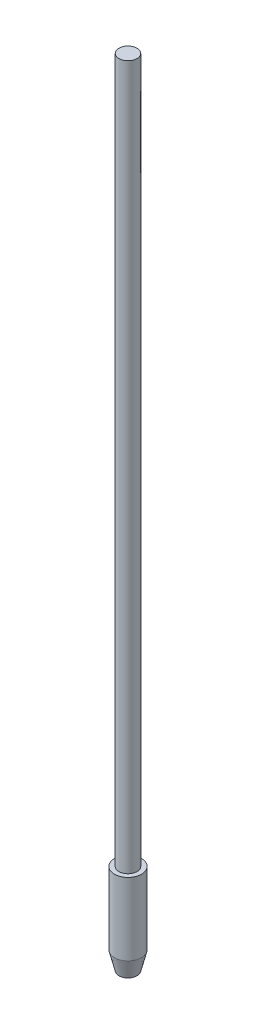
SolidWorks part; units mm, degrees
ref_plane "Front Plane" through (0, 0, 0) normal (0, 0, 1) x (1, 0, 0)
ref_plane "Top Plane" through (0, 0, 0) normal (0, 1, 0) x (1, 0, 0)
ref_plane "Right Plane" through (0, 0, 0) normal (1, 0, 0) x (0, 0, -1)
sketch "Sketch1" plane through (0, 0, 0) normal (0, 1, 0) x (1, 0, 0)
  line L0 (0, 0) -> (640, 0) construction
  line L1 (0, 0) -> (591.2829, 244.9174)
  line L2 (0, 0) -> (591.2829, -244.9174)
  line L3 (0, 0) -> (244.9174, -591.2829)
  line L4 (0, 0) -> (-244.9174, -591.2829)
  line L5 (0, 0) -> (-591.2829, -244.9174)
  line L6 (0, 0) -> (-591.2829, 244.9174)
  line L7 (0, 0) -> (-244.9174, 591.2829)
  line L8 (0, 0) -> (244.9174, 591.2829)
  line L9 (0, 145) -> (55, 145) construction
  line L10 (0, 0) -> (100, 0) construction
  line L11 (0, 0) -> (0, 145) construction
  line L14 (100, 0) -> (100, 145) construction
  circle A0 centre (0, 0) radius 640 construction
  point P15 (0, 0)
  dimension "D1" = 1280
  dimension "D2" = 22.5
  dimension "D4" = 145
  dimension "D5" = 100
  dimension "D6" = 55
  dimension "D3" = 8
sketch "Sketch2" plane through (0, 0, 0) normal (0, 1, 0) x (1, 0, 0)
  line L0 (-486.9956, 169.5033) -> (-66.9956, 169.5033) construction
  line L1 (-188.7141, -86.1278) -> (-188.7141, 241.8722) construction
  line L2 (525.6625, -1048.8053) -> (466.9027, -726.1115) construction
sketch "Sketch3" plane through (0, 0, 0) normal (0, 1, 0) x (1, 0, 0)
  line L0 (0, 0) -> (381.2468, 0) construction
  line L5 (0, 0) -> (0, 199.4415) construction
  line L6 (-10.2736, 158.9263) -> (10.2736, 158.9263)
  line L7 (10.2736, 158.9263) -> (13.1995, 163.9003)
  line L8 (13.1995, 163.9003) -> (45.5131, 148.2994)
  line L9 (45.5131, 148.2994) -> (66.2904, 80.9335)
  line L10 (66.2904, 80.9335) -> (73.8622, 80.9335)
  line L11 (73.8622, 80.9335) -> (86.8684, 42.4396)
  line L12 (86.8684, 42.4396) -> (86.8684, 30.0712)
  line L13 (86.8684, 30.0712) -> (81.3965, 24.5993)
  line L14 (81.3965, 24.5993) -> (81.3965, -24.5993)
  line L15 (-5.8349, 67.4929) -> (5.8349, 67.4929) construction
  line L16 (16.6008, 64.1674) -> (16.6008, 27.6557) construction
  line L17 (16.6008, 27.6557) -> (13.2646, 22.809) construction
  line L18 (13.2646, 22.809) -> (13.2646, -22.809) construction
  line L19 (5.8349, 128.0146) -> (5.8349, 107.4452)
  line L22 (5.8349, 107.4452) -> (9.2702, 107.4452)
  line L25 (9.2702, 107.4452) -> (10.663, 103.7163)
  line L26 (10.663, 103.7163) -> (20.7578, 101.0699)
  line L27 (20.7578, 101.0699) -> (32.199, 111.7601)
  line L28 (32.199, 111.7601) -> (32.199, 123.5038)
  line L29 (32.199, 123.5038) -> (24.9078, 123.5038)
  line L30 (24.9078, 123.5038) -> (13.8412, 132.5856)
  line L31 (13.8412, 132.5856) -> (9.2702, 132.5856)
  line L32 (9.2702, 132.5856) -> (5.8349, 128.0146)
  line L33 (41.9414, 39.7891) -> (51.4866, 54.1602)
  line L34 (51.4866, 54.1602) -> (55.4027, 54.1602)
  line L35 (55.4027, 54.1602) -> (58.1637, 51.3993)
  line L36 (58.1637, 51.3993) -> (58.1637, 43.1872)
  line L37 (58.1637, 43.1872) -> (66.3555, 28.462)
  line L38 (66.3555, 28.462) -> (66.3555, 24.0728)
  line L39 (66.3555, 24.0728) -> (62.2596, 17.9061)
  line L40 (62.2596, 17.9061) -> (47.8497, 18.1669)
  line L41 (47.8497, 18.1669) -> (41.9414, 27.1878)
  line L42 (41.9414, 27.1878) -> (41.9414, 39.7891)
  line L43 (-41.9414, 27.1878) -> (-41.9414, 39.7891)
  line L44 (-47.8497, 18.1669) -> (-41.9414, 27.1878)
  line L45 (-62.2596, 17.9061) -> (-47.8497, 18.1669)
  line L46 (-66.3555, 24.0728) -> (-62.2596, 17.9061)
  line L47 (-66.3555, 28.462) -> (-66.3555, 24.0728)
  line L48 (-58.1637, 43.1872) -> (-66.3555, 28.462)
  line L49 (-58.1637, 51.3993) -> (-58.1637, 43.1872)
  line L50 (-55.4027, 54.1602) -> (-58.1637, 51.3993)
  line L51 (-51.4866, 54.1602) -> (-55.4027, 54.1602)
  line L52 (-41.9414, 39.7891) -> (-51.4866, 54.1602)
  line L53 (-9.2702, 132.5856) -> (-5.8349, 128.0146)
  line L54 (-13.8412, 132.5856) -> (-9.2702, 132.5856)
  line L55 (-24.9078, 123.5038) -> (-13.8412, 132.5856)
  line L56 (-32.199, 123.5038) -> (-24.9078, 123.5038)
  line L57 (-32.199, 111.7601) -> (-32.199, 123.5038)
  line L58 (-20.7578, 101.0699) -> (-32.199, 111.7601)
  line L59 (-10.663, 103.7163) -> (-20.7578, 101.0699)
  line L60 (-9.2702, 107.4452) -> (-10.663, 103.7163)
  line L61 (-5.8349, 107.4452) -> (-9.2702, 107.4452)
  line L62 (-5.8349, 128.0146) -> (-5.8349, 107.4452)
  line L63 (-13.2646, 22.809) -> (-13.2646, -22.809) construction
  line L64 (-16.6008, 27.6557) -> (-13.2646, 22.809) construction
  line L65 (-16.6008, 64.1674) -> (-16.6008, 27.6557) construction
  line L66 (-81.3965, 24.5993) -> (-81.3965, -24.5993)
  line L67 (-86.8684, 30.0712) -> (-81.3965, 24.5993)
  line L68 (-86.8684, 42.4396) -> (-86.8684, 30.0712)
  line L69 (-73.8622, 80.9335) -> (-86.8684, 42.4396)
  line L70 (-66.2904, 80.9335) -> (-73.8622, 80.9335)
  line L71 (-45.5131, 148.2994) -> (-66.2904, 80.9335)
  line L72 (-13.1995, 163.9003) -> (-45.5131, 148.2994)
  line L73 (-10.2736, 158.9263) -> (-13.1995, 163.9003)
  line L74 (-10.2736, -158.9263) -> (-13.1995, -163.9003)
  line L75 (-13.1995, -163.9003) -> (-45.5131, -148.2994)
  line L76 (-45.5131, -148.2994) -> (-66.2904, -80.9335)
  line L77 (-66.2904, -80.9335) -> (-73.8622, -80.9335)
  line L78 (-73.8622, -80.9335) -> (-86.8684, -42.4396)
  line L79 (-86.8684, -42.4396) -> (-86.8684, -30.0712)
  line L80 (-86.8684, -30.0712) -> (-81.3965, -24.5993)
  line L81 (-16.6008, -64.1674) -> (-16.6008, -27.6557) construction
  line L82 (-16.6008, -27.6557) -> (-13.2646, -22.809) construction
  line L83 (-5.8349, -128.0146) -> (-5.8349, -107.4452)
  line L84 (-5.8349, -107.4452) -> (-9.2702, -107.4452)
  line L85 (-9.2702, -107.4452) -> (-10.663, -103.7163)
  line L86 (-10.663, -103.7163) -> (-20.7578, -101.0699)
  line L87 (-20.7578, -101.0699) -> (-32.199, -111.7601)
  line L88 (-32.199, -111.7601) -> (-32.199, -123.5038)
  line L89 (-32.199, -123.5038) -> (-24.9078, -123.5038)
  line L90 (-24.9078, -123.5038) -> (-13.8412, -132.5856)
  line L91 (-13.8412, -132.5856) -> (-9.2702, -132.5856)
  line L92 (-9.2702, -132.5856) -> (-5.8349, -128.0146)
  line L93 (-41.9414, -39.7891) -> (-51.4866, -54.1602)
  line L94 (-51.4866, -54.1602) -> (-55.4027, -54.1602)
  line L95 (-55.4027, -54.1602) -> (-58.1637, -51.3993)
  line L96 (-58.1637, -51.3993) -> (-58.1637, -43.1872)
  line L97 (-58.1637, -43.1872) -> (-66.3555, -28.462)
  line L98 (-66.3555, -28.462) -> (-66.3555, -24.0728)
  line L99 (-66.3555, -24.0728) -> (-62.2596, -17.9061)
  line L100 (-62.2596, -17.9061) -> (-47.8497, -18.1669)
  line L101 (-47.8497, -18.1669) -> (-41.9414, -27.1878)
  line L102 (-41.9414, -27.1878) -> (-41.9414, -39.7891)
  line L103 (41.9414, -27.1878) -> (41.9414, -39.7891)
  line L104 (47.8497, -18.1669) -> (41.9414, -27.1878)
  line L105 (62.2596, -17.9061) -> (47.8497, -18.1669)
  line L106 (66.3555, -24.0728) -> (62.2596, -17.9061)
  line L107 (66.3555, -28.462) -> (66.3555, -24.0728)
  line L108 (58.1637, -43.1872) -> (66.3555, -28.462)
  line L109 (58.1637, -51.3993) -> (58.1637, -43.1872)
  line L110 (55.4027, -54.1602) -> (58.1637, -51.3993)
  line L111 (51.4866, -54.1602) -> (55.4027, -54.1602)
  line L112 (41.9414, -39.7891) -> (51.4866, -54.1602)
  line L113 (9.2702, -132.5856) -> (5.8349, -128.0146)
  line L114 (13.8412, -132.5856) -> (9.2702, -132.5856)
  line L115 (24.9078, -123.5038) -> (13.8412, -132.5856)
  line L116 (32.199, -123.5038) -> (24.9078, -123.5038)
  line L117 (32.199, -111.7601) -> (32.199, -123.5038)
  line L118 (20.7578, -101.0699) -> (32.199, -111.7601)
  line L119 (10.663, -103.7163) -> (20.7578, -101.0699)
  line L120 (9.2702, -107.4452) -> (10.663, -103.7163)
  line L121 (5.8349, -107.4452) -> (9.2702, -107.4452)
  line L122 (5.8349, -128.0146) -> (5.8349, -107.4452)
  line L123 (16.6008, -27.6557) -> (13.2646, -22.809) construction
  line L124 (16.6008, -64.1674) -> (16.6008, -27.6557) construction
  line L125 (-5.8349, -67.4929) -> (5.8349, -67.4929) construction
  line L126 (86.8684, -30.0712) -> (81.3965, -24.5993)
  line L127 (86.8684, -42.4396) -> (86.8684, -30.0712)
  line L128 (73.8622, -80.9335) -> (86.8684, -42.4396)
  line L129 (66.2904, -80.9335) -> (73.8622, -80.9335)
  line L130 (45.5131, -148.2994) -> (66.2904, -80.9335)
  line L131 (13.1995, -163.9003) -> (45.5131, -148.2994)
  line L132 (10.2736, -158.9263) -> (13.1995, -163.9003)
  line L133 (-10.2736, -158.9263) -> (10.2736, -158.9263)
  line L134 (-5.3457, 68.4929) -> (5.3457, 68.4929)
  line L135 (17.6008, 64.1674) -> (17.6008, 27.3448)
  line L136 (17.6008, 27.3448) -> (14.2646, 22.498)
  line L137 (14.2646, 22.498) -> (14.2646, -22.498)
  line L138 (-17.6008, 64.1674) -> (-17.6008, 27.3448)
  line L139 (-17.6008, 27.3448) -> (-14.2646, 22.498)
  line L140 (-5.3457, 68.4929) -> (5.3457, 68.4929) construction
  line L141 (14.2646, 22.498) -> (14.2646, -22.498) construction
  line L142 (17.6008, -27.3448) -> (14.2646, -22.498) construction
  line L143 (17.6008, -64.1674) -> (17.6008, -27.3448) construction
  line L144 (-14.2646, 22.498) -> (-14.2646, -22.498)
  line L145 (17.6008, -64.1674) -> (17.6008, -27.3448)
  line L146 (17.6008, -27.3448) -> (14.2646, -22.498)
  line L147 (-17.6008, -27.3448) -> (-14.2646, -22.498)
  line L148 (-17.6008, -64.1674) -> (-17.6008, -27.3448)
  line L149 (-5.3457, -68.4929) -> (5.3457, -68.4929)
  arc A0 (5.8349, 67.4929) -> (16.6008, 64.0252) centre (10.663, 64.0364) cw construction
  arc A5 (-5.8349, 67.4929) -> (-16.6008, 64.0252) centre (-10.663, 64.0364) ccw construction
  arc A6 (-5.8349, -67.4929) -> (-16.6008, -64.0252) centre (-10.663, -64.0364) cw construction
  arc A7 (5.8349, -67.4929) -> (16.6008, -64.0252) centre (10.663, -64.0364) ccw construction
  arc A8 (-5.3457, 68.4929) -> (-17.6008, 64.0234) centre (-10.663, 64.0364) ccw
  arc A9 (5.3457, 68.4929) -> (17.6008, 64.0234) centre (10.663, 64.0364) cw
  arc A10 (-5.3457, 68.4929) -> (-17.6008, 64.0234) centre (-10.663, 64.0364) ccw construction
  arc A11 (5.3457, -68.4929) -> (17.6008, -64.0234) centre (10.663, -64.0364) ccw
  arc A12 (-5.3457, -68.4929) -> (-17.6008, -64.0234) centre (-10.663, -64.0364) cw
  ellipse E0 centre (11.3851, 149.6854) end of major axis (12.0553, 155.2702) minor radius 3.0047
  ellipse E1 centre (33.6925, 82.363) end of major axis (41.1096, 88.3895) minor radius 4.3287
  ellipse E2 centre (44.8955, 74.0187) end of major axis (51.4866, 79.374) minor radius 4.6847
  ellipse E3 centre (66.3555, 66.447) end of major axis (67.1471, 72.2416) minor radius 3.5711
  ellipse E4 centre (-66.3555, 66.447) end of major axis (-67.1471, 72.2416) minor radius 3.5711
  ellipse E5 centre (-44.8955, 74.0187) end of major axis (-51.4866, 79.374) minor radius 4.6847
  ellipse E6 centre (-33.6925, 82.363) end of major axis (-41.1096, 88.3895) minor radius 4.3287
  ellipse E7 centre (-11.3851, 149.6854) end of major axis (-12.0553, 155.2702) minor radius 3.0047
  ellipse E8 centre (-11.3851, -149.6854) end of major axis (-12.0553, -155.2702) minor radius 3.0047
  ellipse E9 centre (-33.6925, -82.363) end of major axis (-41.1096, -88.3895) minor radius 4.3287
  ellipse E10 centre (-44.8955, -74.0187) end of major axis (-51.4866, -79.374) minor radius 4.6847
  ellipse E11 centre (-66.3555, -66.447) end of major axis (-67.1471, -72.2416) minor radius 3.5711
  ellipse E12 centre (66.3555, -66.447) end of major axis (67.1471, -72.2416) minor radius 3.5711
  ellipse E13 centre (44.8955, -74.0187) end of major axis (51.4866, -79.374) minor radius 4.6847
  ellipse E14 centre (33.6925, -82.363) end of major axis (41.1096, -88.3895) minor radius 4.3287
  ellipse E15 centre (11.3851, -149.6854) end of major axis (12.0553, -155.2702) minor radius 3.0047
  point P117 (0, 67.4929)
  point P126 (0, 158.9263)
  point P180 (0, -158.9263)
  point P181 (0, -67.4929)
  point P190 (-81.3965, 0)
  point P193 (-13.2646, 0)
  point P234 (13.2646, 0)
  point P237 (81.3965, 0)
  point P261 (0, 68.4929)
  point P271 (14.2646, 0)
  point P274 (-14.2646, 0)
  dimension "D1" = 1
sketch "Sketch4" plane through (0, 0, 0) normal (0, 1, 0) x (1, 0, 0)
  line L0 (0, 0) -> (81.2255, 0) construction
  line L1 (0, 0) -> (0, 97.3086) construction
  line L2 (0, 0) -> (0, 199.4415) construction
  line L3 (-10.1399, 86.6928) -> (10.1399, 86.6928)
  line L4 (10.1399, 86.6928) -> (16.0235, 80.8091)
  line L5 (16.0235, 80.8091) -> (23.9736, 57.3032)
  line L6 (23.9736, 57.3032) -> (23.9736, 47.8894)
  line L7 (23.9736, 47.8894) -> (21.6776, 47.8894)
  line L8 (21.6776, 47.8894) -> (21.6776, 27.2256)
  line L9 (21.6776, 27.2256) -> (27.5382, 22.1416)
  line L10 (27.5382, 22.1416) -> (27.5382, 14.9676)
  line L11 (27.5382, 14.9676) -> (23.9736, 10.8585)
  line L12 (23.9736, 10.8585) -> (23.9736, -10.8585)
  line L13 (-23.9736, 10.8585) -> (-23.9736, -10.8585)
  line L14 (-27.5382, 14.9676) -> (-23.9736, 10.8585)
  line L15 (-27.5382, 22.1416) -> (-27.5382, 14.9676)
  line L16 (-21.6776, 27.2256) -> (-27.5382, 22.1416)
  line L17 (-21.6776, 47.8894) -> (-21.6776, 27.2256)
  line L18 (-23.9736, 47.8894) -> (-21.6776, 47.8894)
  line L19 (-23.9736, 57.3032) -> (-23.9736, 47.8894)
  line L20 (-16.0235, 80.8091) -> (-23.9736, 57.3032)
  line L21 (-10.1399, 86.6928) -> (-16.0235, 80.8091)
  line L22 (-10.1399, -86.6928) -> (-16.0235, -80.8091)
  line L23 (-16.0235, -80.8091) -> (-23.9736, -57.3032)
  line L24 (-23.9736, -57.3032) -> (-23.9736, -47.8894)
  line L25 (-23.9736, -47.8894) -> (-21.6776, -47.8894)
  line L26 (-21.6776, -47.8894) -> (-21.6776, -27.2256)
  line L27 (-21.6776, -27.2256) -> (-27.5382, -22.1416)
  line L28 (-27.5382, -22.1416) -> (-27.5382, -14.9676)
  line L29 (-27.5382, -14.9676) -> (-23.9736, -10.8585)
  line L30 (27.5382, -14.9676) -> (23.9736, -10.8585)
  line L31 (27.5382, -22.1416) -> (27.5382, -14.9676)
  line L32 (21.6776, -27.2256) -> (27.5382, -22.1416)
  line L33 (21.6776, -47.8894) -> (21.6776, -27.2256)
  line L34 (23.9736, -47.8894) -> (21.6776, -47.8894)
  line L35 (23.9736, -57.3032) -> (23.9736, -47.8894)
  line L36 (16.0235, -80.8091) -> (23.9736, -57.3032)
  line L37 (10.1399, -86.6928) -> (16.0235, -80.8091)
  line L38 (-10.1399, -86.6928) -> (10.1399, -86.6928)
  point P3 (0, -86.6928)
  point P27 (0, 86.6928)
  point P37 (-23.9736, 0)
  point P38 (23.9736, 0)
sketch "Sketch5" plane through (0, 0, 0) normal (0, 1, 0) x (1, 0, 0)
  line L0 (0, 68.4929) -> (0, 86.6928) construction
  line L1 (15.4511, 110) -> (223.3697, 546.0887)
  line L2 (0, 0) -> (0, 251.8084) construction
  line L3 (0, 110) -> (47.9221, 110) construction
  line L5 (244.9174, 616.9519) -> (262.4572, 609.0616) construction
  line L6 (262.4572, 609.0616) -> (269.1565, 599.6825) construction
  line L7 (269.1565, 599.6825) -> (256.4381, 571.4103) construction
  line L8 (256.4381, 571.4103) -> (244.9174, 563.1812) construction
  line L9 (244.9174, 563.1812) -> (221.08, 517.0826) construction
  line L10 (221.08, 517.0826) -> (201.6817, 527.1134) construction
  line L11 (201.6817, 527.1134) -> (221.6088, 571.4103) construction
  line L12 (221.6088, 571.4103) -> (218.2415, 584.6462) construction
  line L13 (218.2415, 584.6462) -> (232.4366, 616.2011) construction
  line L14 (232.4366, 616.2011) -> (244.9174, 616.9519) construction
  line L15 (244.9174, 591.2829) -> (309.3694, 564.586) construction
  line L16 (269.6266, 526.9284) -> (173.6132, 566.6985) construction
  line L18 (0, 0) -> (107.3069, 0) construction
  dimension "D1" = 110
  dimension "D2" = 50
sketch "Sketch6" plane through (0, 0, 0) normal (0, 1, 0) x (1, 0, 0)
  line L1 (27.9119, 24.7148) -> (544.6401, 226.6863)
  circle A0 centre (0, 0) radius 640 construction
  circle A1 centre (0, 0) radius 640 construction
  circle A3 centre (0, 0) radius 589.9318 construction
  dimension "D1" = 50.0682
sketch "Sketch19" plane through (0, 0, 0) normal (0, 1, 0) x (1, 0, 0)
  line L0 (128.4599, 309.2664) -> (271.805, 137.4916) construction
  line L2 (282.2713, 110.7144) -> (270.4398, 140.9843) construction
  line L5 (26.7343, 104.6204) -> (234.6528, 540.7091)
  line L6 (26.7343, 104.6204) -> (234.6528, 540.7091) construction
  line L7 (4.1679, 115.3796) -> (212.0865, 551.4683)
  line L8 (4.1679, 115.3796) -> (212.0865, 551.4683) construction
  line L9 (20.631, 43.3425) -> (537.3592, 245.3139)
  line L10 (32.4624, 13.0726) -> (549.1907, 215.044)
  line L11 (32.4624, 13.0726) -> (549.1907, 215.044) construction
  line L12 (23.3613, 36.3571) -> (540.0895, 238.3286)
  line L13 (23.3613, 36.3571) -> (540.0895, 238.3286) construction
  line L14 (20.631, 43.3425) -> (537.3592, 245.3139) construction
  line L15 (30.1192, 103.0065) -> (238.0378, 539.0952)
  line L16 (30.1192, 103.0065) -> (238.0378, 539.0952) construction
  line L22 (21.9961, 39.8498) -> (538.7244, 241.8213)
  line L23 (21.9961, 39.8498) -> (538.7244, 241.8213) construction
  line L24 (33.5042, 101.3926) -> (241.4227, 537.4813)
  line L25 (33.5042, 101.3926) -> (241.4227, 537.4813) construction
  circle A0 centre (276.3556, 125.8493) radius 5
  dimension "D6" = 10
  dimension "D1" = 12.5
  dimension "D2" = 12.5
  dimension "D3" = 12.5
  dimension "D4" = 12.5
  dimension "D5" = 16.25
  dimension "D8" = 16.25
  dimension "D10" = 20
  dimension "D11" = 20
extrude "Boss-Extrude1" add sketch "Sketch19" against normal blind 390
sketch "Sketch25" plane through (0, -390, 0) normal (0, -1, 0) x (1, 0, 0)
  circle A0 centre (276.3556, -125.8493) radius 7.5
  dimension "D1" = 15
extrude "Boss-Extrude2" add sketch "Sketch25" along normal blind 40
sketch "Sketch26" plane through (0, -430, 0) normal (0, -1, 0) x (1, 0, 0)
  circle A1 centre (276.3556, -125.8493) radius 7.5
  circle A2 centre (276.3556, -125.8493) radius 7.5
  dimension "D1" = 0
ref_plane "Plane1" through (0, -440, 0) normal (0, -1, 0) x (-1, 0, 0)
sketch "Sketch27" plane through (0, -440, 0) normal (0, -1, 0) x (-1, 0, 0)
  circle A0 centre (-276.3556, 125.8493) radius 7.5 construction
  circle A1 centre (-276.3556, 125.8493) radius 7.5 construction
  circle A2 centre (-276.3556, 125.8493) radius 5
  dimension "D1" = 2.5
loft "Loft1" add profiles "Sketch26", "Sketch27"
